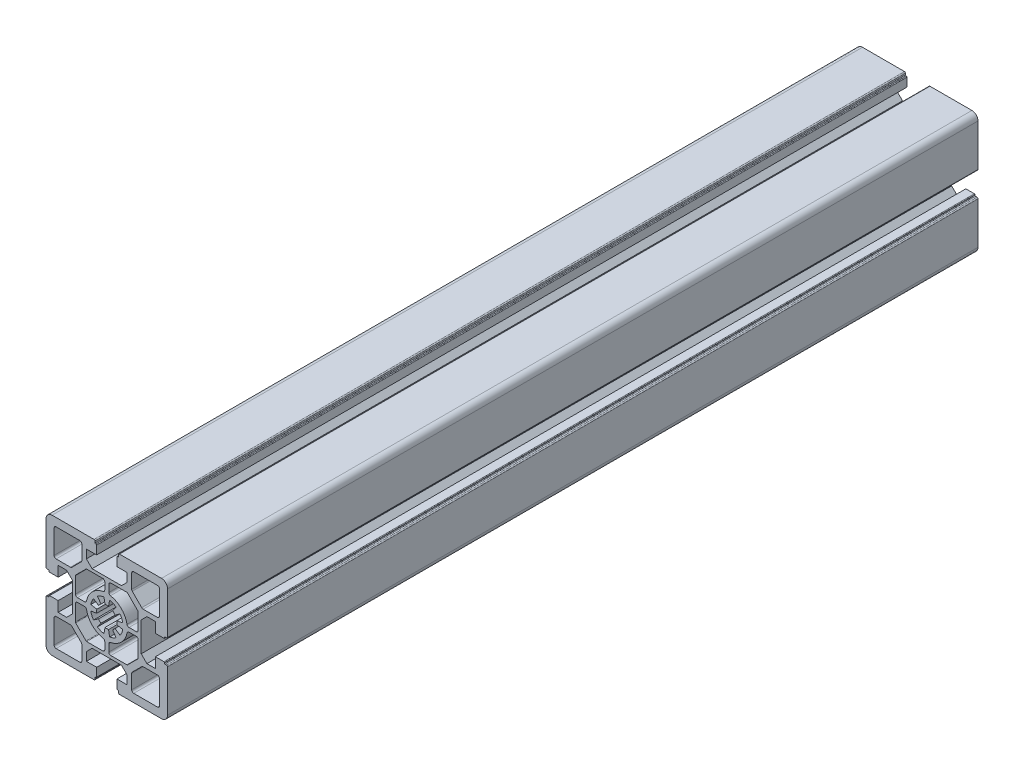
SolidWorks part; units mm, degrees
ref_plane "Front Plane" through (0, 0, 0) normal (0, 0, 1) x (1, 0, 0)
ref_plane "Top Plane" through (0, 0, 0) normal (0, 1, 0) x (1, 0, 0)
ref_plane "Right Plane" through (0, 0, 0) normal (1, 0, 0) x (0, 0, -1)
sketch "Sketch1" plane through (0, 0, 0) normal (0, 0, 1) x (1, 0, 0)
  line L0 (25, 12.3) -> (17.9642, 12.3)
  line L1 (17.2571, 12.5929) -> (12.5929, 17.2571)
  line L2 (12.3, 17.9642) -> (12.3, 25)
  line L3 (25, 26) -> (13.3, 26)
  line L4 (26, 13.3) -> (26, 25)
  line L5 (-0.8683, 4.924) -> (-1.3892, 7.8785)
  line L6 (-4.5886, 6.5532) -> (-2.8679, 4.0958)
  line L7 (-4.0958, 2.8679) -> (-6.5532, 4.5886)
  line L8 (-7.8785, 1.3892) -> (-4.9241, 0.8683)
  line L9 (14.5, 1) -> (10.9691, 1)
  line L10 (15.5, 2) -> (15.5, 9.9003)
  line L11 (15.3535, 10.2538) -> (10.2538, 15.3536)
  line L12 (9.9002, 15.5) -> (2, 15.5)
  line L13 (1, 10.9692) -> (1, 14.5)
  line L14 (7.25, 17) -> (0, 17)
  line L15 (10.05, 19.8) -> (7.25, 17)
  line L16 (10.05, 24) -> (10.05, 19.8)
  line L17 (5, 24) -> (10.05, 24)
  line L18 (5, 28.2) -> (5, 24)
  line L19 (5.5, 28.5) -> (5.3, 28.5)
  line L20 (5.8, 28.8) -> (5.8, 29.5)
  line L21 (27, 30) -> (6.3, 30)
  line L22 (30, 6.3) -> (30, 27)
  line L23 (29.5, 5.8) -> (28.8, 5.8)
  line L24 (28.5, 5.3) -> (28.5, 5.5)
  line L25 (24, 5) -> (28.2, 5)
  line L26 (24, 10.05) -> (24, 5)
  line L27 (19.8, 10.05) -> (24, 10.05)
  line L28 (17, 7.25) -> (19.8, 10.05)
  line L29 (17, 7.25) -> (17, 0)
  line L30 (7.8784, 1.3892) -> (4.924, 0.8683)
  line L31 (4.0957, 2.8679) -> (6.5532, 4.5886)
  line L32 (4.5886, 6.5532) -> (2.8679, 4.0958)
  line L33 (0.8682, 4.924) -> (1.3892, 7.8785)
  line L34 (-25, -12.3) -> (-17.9642, -12.3)
  line L35 (-17.2571, -12.5929) -> (-12.5929, -17.2571)
  line L36 (-12.3, -17.9642) -> (-12.3, -25)
  line L37 (-25, -26) -> (-13.3, -26)
  line L38 (-26, -13.3) -> (-26, -25)
  line L39 (-14.5, -1) -> (-10.9692, -1)
  line L40 (-15.5, -2) -> (-15.5, -9.9002)
  line L41 (-17, 7.25) -> (-17, 0)
  line L42 (-17, 7.25) -> (-19.8, 10.05)
  line L43 (-19.8, 10.05) -> (-24, 10.05)
  line L44 (-24, 10.05) -> (-24, 5)
  line L45 (-24, 5) -> (-28.2, 5)
  line L46 (-28.5, 5.3) -> (-28.5, 5.5)
  line L47 (-29.5, 5.8) -> (-28.8, 5.8)
  line L48 (-30, 6.3) -> (-30, 27)
  line L49 (-27, 30) -> (-6.3, 30)
  line L50 (-5.8, 28.8) -> (-5.8, 29.5)
  line L51 (-5.5, 28.5) -> (-5.3, 28.5)
  line L52 (-5, 28.2) -> (-5, 24)
  line L53 (-5, 24) -> (-10.05, 24)
  line L54 (-10.05, 24) -> (-10.05, 19.8)
  line L55 (-10.05, 19.8) -> (-7.25, 17)
  line L56 (-7.25, 17) -> (0, 17)
  line L57 (-15.3536, -10.2538) -> (-10.2538, -15.3535)
  line L58 (-9.9003, -15.5) -> (-2, -15.5)
  line L59 (-1, -10.9691) -> (-1, -14.5)
  line L60 (-7.25, -17) -> (0, -17)
  line L61 (-10.05, -19.8) -> (-7.25, -17)
  line L62 (-10.05, -24) -> (-10.05, -19.8)
  line L63 (-5, -24) -> (-10.05, -24)
  line L64 (-5, -28.2) -> (-5, -24)
  line L65 (-5.5, -28.5) -> (-5.3, -28.5)
  line L66 (-5.8, -28.8) -> (-5.8, -29.5)
  line L67 (-27, -30) -> (-6.3, -30)
  line L68 (-30, -6.3) -> (-30, -27)
  line L69 (-29.5, -5.8) -> (-28.8, -5.8)
  line L70 (-28.5, -5.3) -> (-28.5, -5.5)
  line L71 (-24, -5) -> (-28.2, -5)
  line L72 (-24, -10.05) -> (-24, -5)
  line L73 (-19.8, -10.05) -> (-24, -10.05)
  line L74 (-17, -7.25) -> (-19.8, -10.05)
  line L75 (-17, 0) -> (-17, -7.25)
  line L76 (0.8682, -4.924) -> (1.3892, -7.8784)
  line L77 (4.5886, -6.5532) -> (2.8679, -4.0957)
  line L78 (4.0957, -2.8679) -> (6.5532, -4.5886)
  line L79 (7.8784, -1.3892) -> (4.924, -0.8682)
  line L80 (17, 0) -> (17, -7.25)
  line L81 (17, -7.25) -> (19.8, -10.05)
  line L82 (19.8, -10.05) -> (24, -10.05)
  line L83 (24, -10.05) -> (24, -5)
  line L84 (24, -5) -> (28.2, -5)
  line L85 (28.5, -5.3) -> (28.5, -5.5)
  line L86 (29.5, -5.8) -> (28.8, -5.8)
  line L87 (30, -6.3) -> (30, -27)
  line L88 (27, -30) -> (6.3, -30)
  line L89 (5.8, -28.8) -> (5.8, -29.5)
  line L90 (5.5, -28.5) -> (5.3, -28.5)
  line L91 (5, -28.2) -> (5, -24)
  line L92 (5, -24) -> (10.05, -24)
  line L93 (10.05, -24) -> (10.05, -19.8)
  line L94 (10.05, -19.8) -> (7.25, -17)
  line L95 (7.25, -17) -> (0, -17)
  line L96 (1, -10.9691) -> (1, -14.5)
  line L97 (9.9002, -15.5) -> (2, -15.5)
  line L98 (15.3535, -10.2538) -> (10.2538, -15.3535)
  line L99 (15.5, -2) -> (15.5, -9.9002)
  line L100 (-1, 10.9692) -> (-1, 14.5)
  line L101 (-9.9003, 15.5) -> (-2, 15.5)
  line L102 (-15.3536, 10.2538) -> (-10.2538, 15.3536)
  line L103 (-15.5, 2) -> (-15.5, 9.9003)
  line L104 (-14.5, 1) -> (-10.9692, 1)
  line L105 (-26, 13.3) -> (-26, 25)
  line L106 (-25, 26) -> (-13.3, 26)
  line L107 (-12.3, 17.9642) -> (-12.3, 25)
  line L108 (-17.2571, 12.5929) -> (-12.5929, 17.2571)
  line L109 (-25, 12.3) -> (-17.9642, 12.3)
  line L110 (14.5, -1) -> (10.9691, -1)
  line L111 (-7.8785, -1.3892) -> (-4.9241, -0.8682)
  line L112 (-4.0958, -2.8679) -> (-6.5532, -4.5886)
  line L113 (-4.5886, -6.5532) -> (-2.8679, -4.0957)
  line L114 (-0.8683, -4.924) -> (-1.3892, -7.8784)
  line L115 (26, -13.3) -> (26, -25)
  line L116 (25, -26) -> (13.3, -26)
  line L117 (12.3, -17.9642) -> (12.3, -25)
  line L118 (17.2571, -12.5929) -> (12.5929, -17.2571)
  line L119 (25, -12.3) -> (17.9642, -12.3)
  line L120 (0, 0) -> (0, 50.387) construction
  line L121 (0, 0) -> (0, -41.9308) construction
  line L122 (0, 0) -> (51.9943, 0) construction
  line L123 (0, 0) -> (-54.8745, 0) construction
  arc A0 (17.9642, 12.3) -> (17.2571, 12.5929) centre (17.9642, 13.3) cw
  arc A1 (12.5929, 17.2571) -> (12.3, 17.9642) centre (13.3, 17.9642) cw
  arc A2 (12.3, 25) -> (13.3, 26) centre (13.3, 25) cw
  arc A3 (25, 26) -> (26, 25) centre (25, 25) cw
  arc A4 (26, 13.3) -> (25, 12.3) centre (25, 13.3) cw
  arc A5 (0, 5) -> (-0.8683, 4.924) centre (0, 0) ccw
  arc A6 (-1.3892, 7.8785) -> (-4.5886, 6.5532) centre (0, 0) ccw
  arc A7 (-2.8679, 4.0958) -> (-4.0958, 2.8679) centre (0, 0) ccw
  arc A8 (-6.5532, 4.5886) -> (-7.8785, 1.3892) centre (0, 0) ccw
  arc A9 (-4.9241, 0.8683) -> (-4.9241, -0.8682) centre (0, 0) ccw
  arc A10 (15.5, 2) -> (14.5, 1) centre (14.5, 2) cw
  arc A11 (15.3535, 10.2538) -> (15.5, 9.9003) centre (15, 9.9003) cw
  arc A12 (9.9002, 15.5) -> (10.2538, 15.3536) centre (9.9002, 15) cw
  arc A13 (1, 14.5) -> (2, 15.5) centre (2, 14.5) cw
  arc A14 (1.8206, 9.9854) -> (1, 10.9692) centre (2, 10.9692) cw
  arc A15 (1.8206, 9.9854) -> (9.9853, 1.8206) centre (0, 0) cw
  arc A16 (10.9691, 1) -> (9.9853, 1.8206) centre (10.9691, 2) cw
  arc A17 (5, 28.2) -> (5.3, 28.5) centre (5.3, 28.2) cw
  arc A18 (5.8, 28.8) -> (5.5, 28.5) centre (5.5, 28.8) cw
  arc A19 (5.8, 29.5) -> (6.3, 30) centre (6.3, 29.5) cw
  arc A20 (27, 30) -> (30, 27) centre (27, 27) cw
  arc A21 (30, 6.3) -> (29.5, 5.8) centre (29.5, 6.3) cw
  arc A22 (28.5, 5.5) -> (28.8, 5.8) centre (28.8, 5.5) cw
  arc A23 (28.5, 5.3) -> (28.2, 5) centre (28.2, 5.3) cw
  arc A24 (4.924, 0.8683) -> (4.924, -0.8682) centre (0, 0) cw
  arc A25 (6.5532, 4.5886) -> (7.8784, 1.3892) centre (0, 0) cw
  arc A26 (2.8679, 4.0958) -> (4.0957, 2.8679) centre (0, 0) cw
  arc A27 (1.3892, 7.8785) -> (4.5886, 6.5532) centre (0, 0) cw
  arc A28 (-28.5, 5.3) -> (-28.2, 5) centre (-28.2, 5.3) ccw
  arc A29 (-28.5, 5.5) -> (-28.8, 5.8) centre (-28.8, 5.5) ccw
  arc A30 (-30, 6.3) -> (-29.5, 5.8) centre (-29.5, 6.3) ccw
  arc A31 (-27, 30) -> (-30, 27) centre (-27, 27) ccw
  arc A32 (-5.8, 29.5) -> (-6.3, 30) centre (-6.3, 29.5) ccw
  arc A33 (-5.8, 28.8) -> (-5.5, 28.5) centre (-5.5, 28.8) ccw
  arc A34 (-5, 28.2) -> (-5.3, 28.5) centre (-5.3, 28.2) ccw
  arc A35 (0, 5) -> (0.8682, 4.924) centre (0, 0) cw
  arc A36 (-17.9642, -12.3) -> (-17.2571, -12.5929) centre (-17.9642, -13.3) cw
  arc A37 (-12.5929, -17.2571) -> (-12.3, -17.9642) centre (-13.3, -17.9642) cw
  arc A38 (-12.3, -25) -> (-13.3, -26) centre (-13.3, -25) cw
  arc A39 (-25, -26) -> (-26, -25) centre (-25, -25) cw
  arc A40 (-26, -13.3) -> (-25, -12.3) centre (-25, -13.3) cw
  arc A41 (-15.5, -2) -> (-14.5, -1) centre (-14.5, -2) cw
  arc A42 (-15.3536, -10.2538) -> (-15.5, -9.9002) centre (-15, -9.9002) cw
  arc A43 (-9.9003, -15.5) -> (-10.2538, -15.3535) centre (-9.9003, -15) cw
  arc A44 (-1, -14.5) -> (-2, -15.5) centre (-2, -14.5) cw
  arc A45 (-1.8206, -9.9853) -> (-1, -10.9691) centre (-2, -10.9691) cw
  arc A46 (-1.8206, -9.9853) -> (-9.9854, -1.8206) centre (0, 0) cw
  arc A47 (-10.9692, -1) -> (-9.9854, -1.8206) centre (-10.9692, -2) cw
  arc A48 (0, -4.9999) -> (0.8682, -4.924) centre (0, 0) ccw
  arc A49 (-5, -28.2) -> (-5.3, -28.5) centre (-5.3, -28.2) cw
  arc A50 (-5.8, -28.8) -> (-5.5, -28.5) centre (-5.5, -28.8) cw
  arc A51 (-5.8, -29.5) -> (-6.3, -30) centre (-6.3, -29.5) cw
  arc A52 (-27, -30) -> (-30, -27) centre (-27, -27) cw
  arc A53 (-30, -6.3) -> (-29.5, -5.8) centre (-29.5, -6.3) cw
  arc A54 (-28.5, -5.5) -> (-28.8, -5.8) centre (-28.8, -5.5) cw
  arc A55 (-28.5, -5.3) -> (-28.2, -5) centre (-28.2, -5.3) cw
  arc A56 (1.3892, -7.8784) -> (4.5886, -6.5532) centre (0, 0) ccw
  arc A57 (2.8679, -4.0957) -> (4.0957, -2.8679) centre (0, 0) ccw
  arc A58 (6.5532, -4.5886) -> (7.8784, -1.3892) centre (0, 0) ccw
  arc A59 (28.5, -5.3) -> (28.2, -5) centre (28.2, -5.3) ccw
  arc A60 (28.5, -5.5) -> (28.8, -5.8) centre (28.8, -5.5) ccw
  arc A61 (30, -6.3) -> (29.5, -5.8) centre (29.5, -6.3) ccw
  arc A62 (27, -30) -> (30, -27) centre (27, -27) ccw
  arc A63 (5.8, -29.5) -> (6.3, -30) centre (6.3, -29.5) ccw
  arc A64 (5.8, -28.8) -> (5.5, -28.5) centre (5.5, -28.8) ccw
  arc A65 (5, -28.2) -> (5.3, -28.5) centre (5.3, -28.2) ccw
  arc A66 (10.9691, -1) -> (9.9853, -1.8206) centre (10.9691, -2) ccw
  arc A67 (1.8206, -9.9853) -> (9.9853, -1.8206) centre (0, 0) ccw
  arc A68 (-10.9692, 1) -> (-9.9854, 1.8206) centre (-10.9692, 2) ccw
  arc A69 (-1.8206, 9.9854) -> (-9.9854, 1.8206) centre (0, 0) ccw
  arc A70 (-1.8206, 9.9854) -> (-1, 10.9692) centre (-2, 10.9692) ccw
  arc A71 (-1, 14.5) -> (-2, 15.5) centre (-2, 14.5) ccw
  arc A72 (-9.9003, 15.5) -> (-10.2538, 15.3536) centre (-9.9003, 15) ccw
  arc A73 (-15.3536, 10.2538) -> (-15.5, 9.9003) centre (-15, 9.9003) ccw
  arc A74 (-15.5, 2) -> (-14.5, 1) centre (-14.5, 2) ccw
  arc A75 (-26, 13.3) -> (-25, 12.3) centre (-25, 13.3) ccw
  arc A76 (-25, 26) -> (-26, 25) centre (-25, 25) ccw
  arc A77 (-12.3, 25) -> (-13.3, 26) centre (-13.3, 25) ccw
  arc A78 (-12.5929, 17.2571) -> (-12.3, 17.9642) centre (-13.3, 17.9642) ccw
  arc A79 (-17.9642, 12.3) -> (-17.2571, 12.5929) centre (-17.9642, 13.3) ccw
  arc A80 (1.8206, -9.9853) -> (1, -10.9691) centre (2, -10.9691) ccw
  arc A81 (1, -14.5) -> (2, -15.5) centre (2, -14.5) ccw
  arc A82 (9.9002, -15.5) -> (10.2538, -15.3535) centre (9.9002, -15) ccw
  arc A83 (15.3535, -10.2538) -> (15.5, -9.9002) centre (15, -9.9002) ccw
  arc A84 (15.5, -2) -> (14.5, -1) centre (14.5, -2) ccw
  arc A85 (-6.5532, -4.5886) -> (-7.8785, -1.3892) centre (0, 0) cw
  arc A86 (-2.8679, -4.0957) -> (-4.0958, -2.8679) centre (0, 0) cw
  arc A87 (-1.3892, -7.8784) -> (-4.5886, -6.5532) centre (0, 0) cw
  arc A88 (0, -4.9999) -> (-0.8683, -4.924) centre (0, 0) cw
  arc A89 (26, -13.3) -> (25, -12.3) centre (25, -13.3) ccw
  arc A90 (25, -26) -> (26, -25) centre (25, -25) ccw
  arc A91 (12.3, -25) -> (13.3, -26) centre (13.3, -25) ccw
  arc A92 (12.5929, -17.2571) -> (12.3, -17.9642) centre (13.3, -17.9642) ccw
  arc A93 (17.9642, -12.3) -> (17.2571, -12.5929) centre (17.9642, -13.3) ccw
  dimension "D6" = 13
  dimension "D4" = 10
  dimension "D1" = 60
  dimension "D2" = 60
  dimension "D3" = 30
  dimension "D5" = 10
extrude "Base-Extrude" add sketch "Sketch1" against normal blind 400
scale "Escala1" scale about origin uniform scaling yes scale factor 0.5
